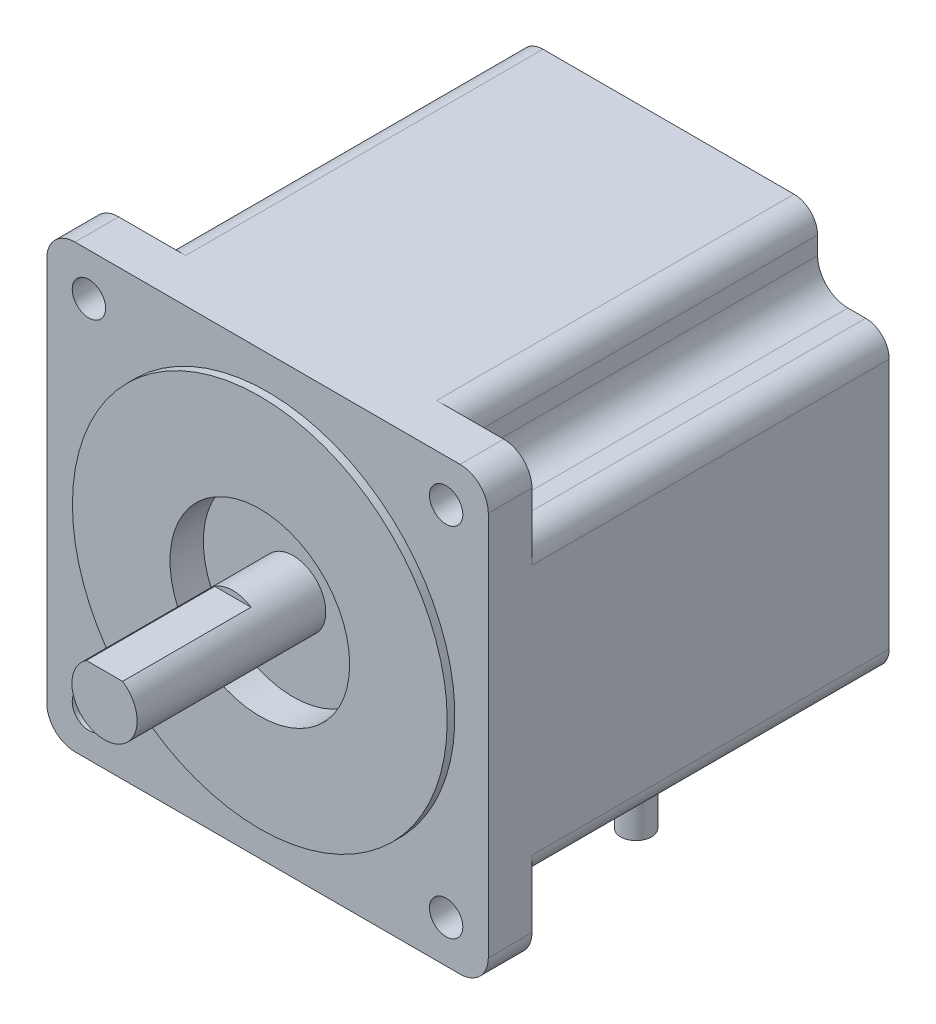
SolidWorks part; units mm, degrees
material "A6061"
ref_plane "前视基准面" through (0, 0, 0) normal (0, 0, 1) x (1, 0, 0)
ref_plane "上视基准面" through (0, 0, 0) normal (0, 1, 0) x (1, 0, 0)
ref_plane "右视基准面" through (0, 0, 0) normal (1, 0, 0) x (0, 0, -1)
ref_plane "基准面1" through (0, 0, -69.6) normal (0, 0, -1) x (-1, 0, 0)
sketch "草图1" plane through (0, 0, -69.6) normal (0, 0, -1) x (-1, 0, 0)
  line L0 (43, 43) -> (-43, 43)
  line L1 (-43, 43) -> (-43, -43)
  line L2 (-43, -43) -> (43, -43)
  line L3 (43, -43) -> (43, 43)
extrude "凸台-拉伸1" add sketch "草图1" against normal blind 78.1
sketch "草图2" plane through (0, 0, 8.5) normal (0, 0, 1) x (1, 0, 0)
  circle A0 centre (0, 0) radius 36.5
extrude "凸台-拉伸2" add sketch "草图2" along normal blind 1.5
hole_wizard "M30 间隙孔1" positions "草图4" profile "草图3" hole size "M30" standard "ANSI Metric"
sketch "草图4" plane through (0, 0, 10) normal (0, 0, 1) x (1, 0, 0)
  point P0 (0, 0)
sketch "草图3" plane through (0, 0, 10) normal (1, 0, 0) x (0, -1, 0)
  line L0 (0, 0) -> (0, 6.5)
  line L1 (0, 6.5) -> (17.5, 6.5)
  line L2 (17.5, 6.5) -> (17.5, 0)
  line L5 (17.5, 0) -> (0, 0)
  line L10 (0, 6.5) -> (-17.5, 6.5) construction
  line L11 (0, -6.35) -> (0, 107.95) construction
  dimension "孔直径" = 35
  dimension "孔深度" = 6.5
  dimension "导头角度" = 180
sketch "草图5" plane through (0, 0, 3.5) normal (0, 0, 1) x (1, 0, 0)
  circle A0 centre (0, 0) radius 6.35
extrude "凸台-拉伸3" add sketch "草图5" along normal blind 36.75
sketch "草图6" plane through (0, 0, 40.25) normal (0, 0, 1) x (1, 0, 0)
  line L0 (-3.5276, 5.28) -> (3.5276, 5.28)
  arc A0 (3.5276, 5.28) -> (-3.5276, 5.28) centre (0, 0) ccw
extrude "切除-拉伸1" cut sketch "草图6" against normal blind 25
sketch "草图7" plane through (-43, 0, 0) normal (-1, 0, 0) x (0, 0, 1)
  line L0 (0, 29.05) -> (0, 43)
  line L1 (0, 43) -> (-69.6, 43)
  line L2 (-69.6, 43) -> (-69.6, 29.05)
  line L3 (-69.6, 29.05) -> (0, 29.05)
extrude "切除-拉伸2" cut sketch "草图7" against normal blind 13.95
sketch "草图8" plane through (0, 43, 0) normal (0, 1, 0) x (-1, 0, 0)
  line L0 (-29.05, 0) -> (-43, 0)
  line L1 (-43, 0) -> (-43, -69.6)
  line L2 (-43, -69.6) -> (-29.05, -69.6)
  line L3 (-29.05, -69.6) -> (-29.05, 0)
extrude "切除-拉伸3" cut sketch "草图8" against normal blind 13.95
sketch "草图9" plane through (0, 0, -69.6) normal (0, 0, -1) x (-1, 0, 0)
  line L0 (43, -29.05) -> (29.05, -29.05)
  line L1 (29.05, -29.05) -> (29.05, -43)
  line L2 (29.05, -43) -> (43, -43)
  line L3 (43, -43) -> (43, -29.05)
extrude "切除-拉伸4" cut sketch "草图9" against normal blind 69.6
sketch "草图10" plane through (0, 0, -69.6) normal (0, 0, -1) x (-1, 0, 0)
  line L0 (-29.05, -43) -> (-29.05, -29.05)
  line L1 (-29.05, -29.05) -> (-43, -29.05)
  line L2 (-43, -29.05) -> (-43, -43)
  line L3 (-43, -43) -> (-29.05, -43)
extrude "切除-拉伸5" cut sketch "草图10" against normal blind 69.6
sketch "草图11" plane through (0, -43, 0) normal (0, -1, 0) x (1, 0, 0)
  line L0 (-5, -56.9876) -> (5, -56.9876)
  line L1 (5, -56.9876) -> (5, -63.2876)
  line L2 (-5, -63.2876) -> (-5, -56.9876)
  arc A0 (5, -63.2876) -> (-5, -63.2876) centre (0, -63.2876) cw
extrude "凸台-拉伸4" add sketch "草图11" along normal blind 2.5
sketch "草图12" plane through (0, -45.5, 0) normal (0, -1, 0) x (1, 0, 0)
  circle A0 centre (0, -63.2876) radius 3
extrude "凸台-拉伸5" add sketch "草图12" along normal blind 27.5
hole_wizard "Ø6.5 (6.5) 直径孔1" positions "草图14" profile "草图13" hole size "Ø6.5" standard "ANSI Metric"
sketch "草图14" plane through (0, 0, 8.5) normal (0, 0, 1) x (1, 0, 0)
  point P0 (34.7897, -34.7897)
sketch "草图13" plane through (34.7897, -34.7897, 8.5) normal (1, 0, 0) x (0, -1, 0)
  line L0 (0, 0) -> (0, 78.1)
  line L1 (0, 78.1) -> (3.25, 78.1)
  line L2 (3.25, 78.1) -> (3.25, 0)
  line L5 (3.25, 0) -> (0, 0)
  line L11 (0, -6.35) -> (0, 107.95) construction
  dimension "通孔孔直径" = 6.5
  dimension "通孔孔深度" = 78.1
hole_wizard "Ø6.5 (6.5) 直径孔2" positions "草图16" profile "草图15" hole size "Ø6.5" standard "ANSI Metric"
sketch "草图16" plane through (0, 0, 0) normal (0, 0, -1) x (-1, 0, 0)
  point P0 (34.7897, -34.7897)
  point P1 (-34.7897, 34.7897)
  point P2 (34.7897, 34.7897)
sketch "草图15" plane through (-34.7897, -34.7897, 0) normal (1, 0, 0) x (0, 1, 0)
  line L0 (0, 0) -> (0, 40.25)
  line L1 (0, 40.25) -> (3.25, 40.25)
  line L2 (3.25, 40.25) -> (3.25, 0)
  line L5 (3.25, 0) -> (0, 0)
  line L11 (0, -6.35) -> (0, 107.95) construction
  dimension "通孔孔直径" = 6.5
  dimension "通孔孔深度" = 40.25
hole_wizard "M27 间隙孔1" positions "草图18" profile "草图17" hole size "M27" standard "ANSI Metric"
sketch "草图18" plane through (0, 0, -69.6) normal (0, 0, -1) x (-1, 0, 0)
  point P0 (0, 0)
sketch "草图17" plane through (0, 0, -69.6) normal (1, 0, 0) x (0, 1, 0)
  line L0 (0, 0) -> (0, 4.4)
  line L1 (0, 4.4) -> (16, 4.4)
  line L2 (16, 4.4) -> (16, 0)
  line L5 (16, 0) -> (0, 0)
  line L10 (0, 4.4) -> (-16, 4.4) construction
  line L11 (0, -6.35) -> (0, 107.95) construction
  dimension "孔直径" = 32
  dimension "孔深度" = 4.4
  dimension "导头角度" = 180
fillet "圆角1" radius 4.6 8 edges at (29.05, 43, -34.8) (-29.05, -43, -34.8) (29.05, -43, -34.8) (43, 29.05, -34.8) (-29.05, 43, -34.8) (43, -29.05, -34.8) (-43, 29.05, -34.8) (-43, -29.05, -34.8)
fillet "圆角2" radius 5.5 4 edges at (43, 43, 4.25) (43, -43, 4.25) (-43, -43, 4.25) (-43, 43, 4.25)
fillet "圆角3" radius 5.9 4 edges at (29.05, -29.05, -34.8) (29.05, 29.05, -34.8) (-29.05, 29.05, -34.8) (-29.05, -29.05, -34.8)
